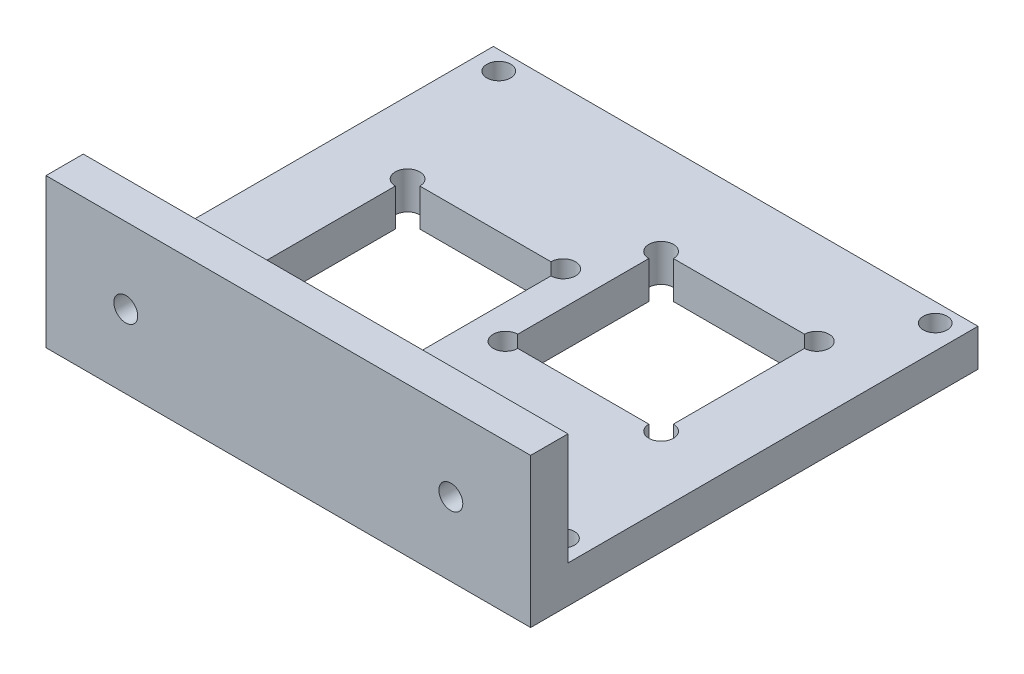
SolidWorks part; units mm, degrees
ref_plane "Front Plane" through (0, 0, 0) normal (0, 0, 1) x (1, 0, 0)
ref_plane "Top Plane" through (0, 0, 0) normal (0, 1, 0) x (1, 0, 0)
ref_plane "Right Plane" through (0, 0, 0) normal (1, 0, 0) x (0, 0, -1)
other "Configuration Table"
sketch "草图1" plane through (0, 0, 0) normal (0, 1, 0) x (1, 0, 0)
  line L0 (-23.2598, 21.6234) -> (35.2802, -28.3766)
  line L1 (-23.2598, 21.6234) -> (35.2802, 21.6234)
  line L2 (-23.2598, 21.6234) -> (-23.2598, -28.3766)
  line L3 (-23.2598, -28.3766) -> (35.2802, -28.3766)
  line L4 (35.2802, 21.6234) -> (35.2802, -28.3766)
  line L6 (-26.4898, -30.8766) -> (38.5102, -30.8766)
  line L7 (-26.4898, -30.8766) -> (-26.4898, 24.1234)
  line L8 (-26.4898, 24.1234) -> (38.5102, 24.1234)
  line L9 (38.5102, -30.8766) -> (38.5102, 24.1234)
  line L10 (-26.4898, -30.8766) -> (38.5102, 24.1234) construction
  line L11 (-26.4898, 24.1234) -> (38.5102, -30.8766) construction
  line L12 (-19.9898, -25.8766) -> (32.0102, -25.8766)
  line L13 (-19.9898, -25.8766) -> (-19.9898, -30.8766)
  line L14 (-19.9898, -30.8766) -> (32.0102, -30.8766)
  line L15 (32.0102, -25.8766) -> (32.0102, -30.8766)
  line L16 (-19.9898, -25.8766) -> (32.0102, -30.8766) construction
  line L17 (-19.9898, -30.8766) -> (32.0102, -25.8766) construction
  circle A0 centre (-23.2598, 21.6234) radius 1.6
  circle A1 centre (35.2802, 21.6234) radius 1.6
  circle A2 centre (35.2802, -28.3766) radius 1.6
  circle A3 centre (-23.2598, -28.3766) radius 1.6
  point P8 (6.0102, -3.3766)
  point P13 (6.0102, -28.3766)
  dimension "D3" = 3.2
  dimension "D4" = 3.2
  dimension "D5" = 3.2
  dimension "D6" = 3.2
  dimension "D1" = 58.54
  dimension "D2" = 50
  dimension "D7" = 65
  dimension "D8" = 55
  dimension "D9" = 52
extrude "凸台-拉伸1" add sketch "草图1" along normal blind 5 contours A2 L4 A1 L1 A0 L0 | A3 L3 L13 L12 L15 A2 L0 A0 L2 | A3 L2 A0 L1 A1 L4 A2 L3 L15 L6 L9 L8 L7 L13
sketch "草图2" plane through (0, 5, 0) normal (0, 1, 0) x (1, 0, 0)
  line L0 (-26.4898, 24.1234) -> (38.5102, 24.1234) construction
  line L1 (8.5702, 11.5634) -> (29.4502, 11.5634)
  line L2 (8.5702, 11.5634) -> (8.5702, -9.3166)
  line L3 (8.5702, -9.3166) -> (29.4502, -9.3166)
  line L4 (29.4502, 11.5634) -> (29.4502, -9.3166)
  line L5 (8.5702, 11.5634) -> (29.4502, -9.3166) construction
  line L6 (8.5702, -9.3166) -> (29.4502, 11.5634) construction
  line L8 (38.5102, -30.8766) -> (38.5102, 24.1234) construction
  line L9 (-16.8512, 2.9788) -> (4.0288, 2.9788)
  line L10 (-16.8512, 2.9788) -> (-16.8512, -17.9012)
  line L11 (-16.8512, -17.9012) -> (4.0288, -17.9012)
  line L12 (4.0288, 2.9788) -> (4.0288, -17.9012)
  circle A0 centre (8.5702, 11.5634) radius 1.65
  circle A1 centre (29.4502, 11.5634) radius 1.65
  circle A2 centre (29.4502, -9.3166) radius 1.65
  circle A3 centre (8.5702, -9.3166) radius 1.65
  circle A4 centre (-16.8512, 2.9788) radius 1.65
  circle A5 centre (4.0288, 2.9788) radius 1.65
  circle A6 centre (4.0288, -17.9012) radius 1.65
  circle A7 centre (-16.8512, -17.9012) radius 1.65
  point P0 (19.0102, 1.1234)
  dimension "D3" = 3.3
  dimension "D4" = 3.3
  dimension "D5" = 3.3
  dimension "D6" = 3.3
  dimension "D1" = 23
  dimension "D2" = 19.5
extrude "切除-拉伸1" cut sketch "草图2" against normal blind 5 contours L12 A5 L9 | A7 L11 A6 L12 A5 L9 A4 L10 | L9 A5 L12 | L11 A6 L12 | L12 A6 L11 | L10 A7 L11 | L11 A7 L10 | L2 A3 L3 | A3 L3 A2 L4 A1 L1 A0 L2 | L4 A1 L1 | L1 A1 L4 | L3 A2 L4 | L4 A2 L3 | L3 A3 L2
sketch "草图3" plane through (0, 0, -24.1234) normal (0, 0, -1) x (-1, 0, 0)
  line L1 (-38.5102, 5) -> (26.4898, 5)
  line L2 (-38.5102, 5) -> (-38.5102, 0)
  line L3 (-38.5102, 0) -> (26.4898, 0)
  line L4 (26.4898, 5) -> (26.4898, 0)
sketch "草图4" plane through (0, 0, 30.8766) normal (0, 0, 1) x (1, 0, 0)
  line L1 (-26.4898, 5) -> (38.5102, 5)
  line L2 (-26.4898, 5) -> (-26.4898, 0)
  line L3 (-26.4898, 0) -> (38.5102, 0)
  line L4 (38.5102, 5) -> (38.5102, 0)
extrude "凸台-拉伸2" add sketch "草图4" along normal blind 5
sketch "草图5" plane through (0, 5, 0) normal (0, 1, 0) x (1, 0, 0)
  line L0 (38.5102, -35.8766) -> (38.5102, 24.1234) construction
  line L1 (-26.4898, -35.8766) -> (38.5102, -35.8766)
  line L2 (-26.4898, -35.8766) -> (-26.4898, -30.8766)
  line L3 (-26.4898, -30.8766) -> (38.5102, -30.8766)
  line L4 (38.5102, -35.8766) -> (38.5102, -30.8766)
extrude "凸台-拉伸3" add sketch "草图5" along normal blind 15 contours L2 L1 L4 L3
sketch "草图6" plane through (0, 0, 30.8766) normal (0, 0, -1) x (-1, 0, 0)
  line L3 (-27.8102, 9.8328) -> (15.7898, 9.8328)
  circle A0 centre (-27.8102, 9.8328) radius 1.6
  circle A1 centre (15.7898, 9.8328) radius 1.6
  point P9 (-6.0102, 9.8328)
extrude "切除-拉伸2" cut sketch "草图6" against normal blind 15
